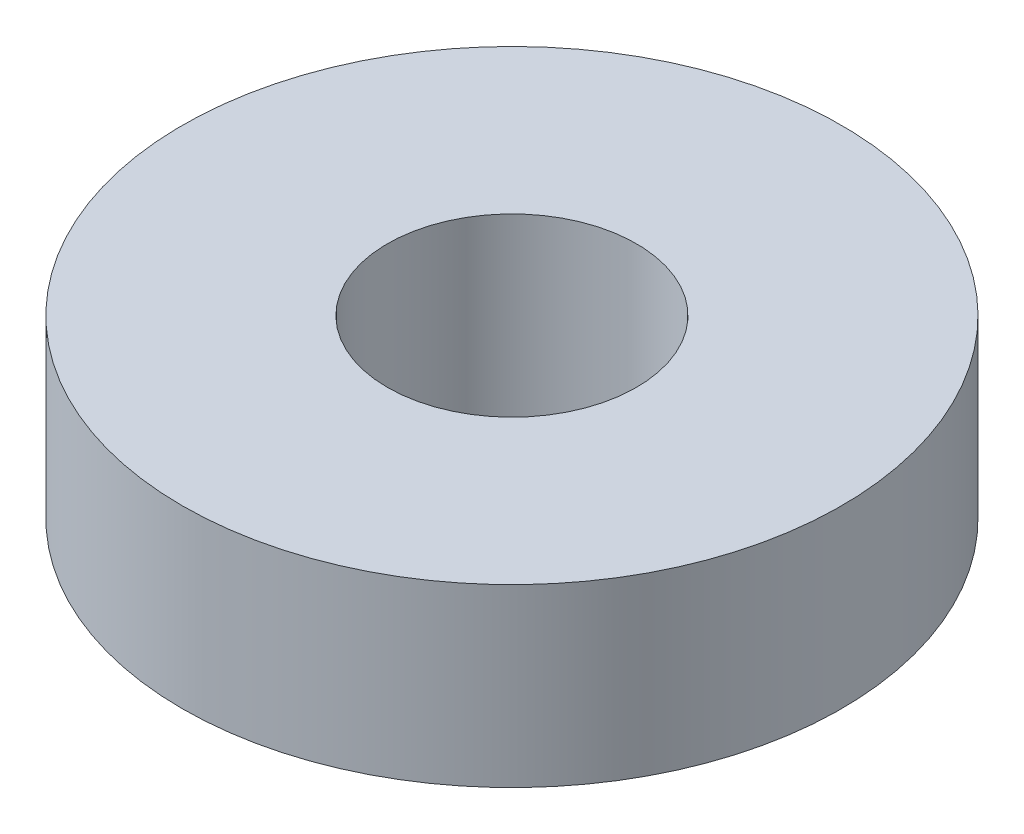
SolidWorks part; units mm, degrees
ref_plane "Front Plane" through (0, 0, 0) normal (0, 0, 1) x (1, 0, 0)
ref_plane "Top Plane" through (0, 0, 0) normal (0, 1, 0) x (1, 0, 0)
ref_plane "Right Plane" through (0, 0, 0) normal (1, 0, 0) x (0, 0, -1)
sketch "Sketch1" plane through (0, 0, 0) normal (0, 1, 0) x (1, 0, 0)
  circle A0 centre (0, 0) radius 22.5
  circle A1 centre (0, 0) radius 8.5
  dimension "D1" = 17
  dimension "D2" = 45
extrude "Boss-Extrude1" add sketch "Sketch1" along normal blind 12
